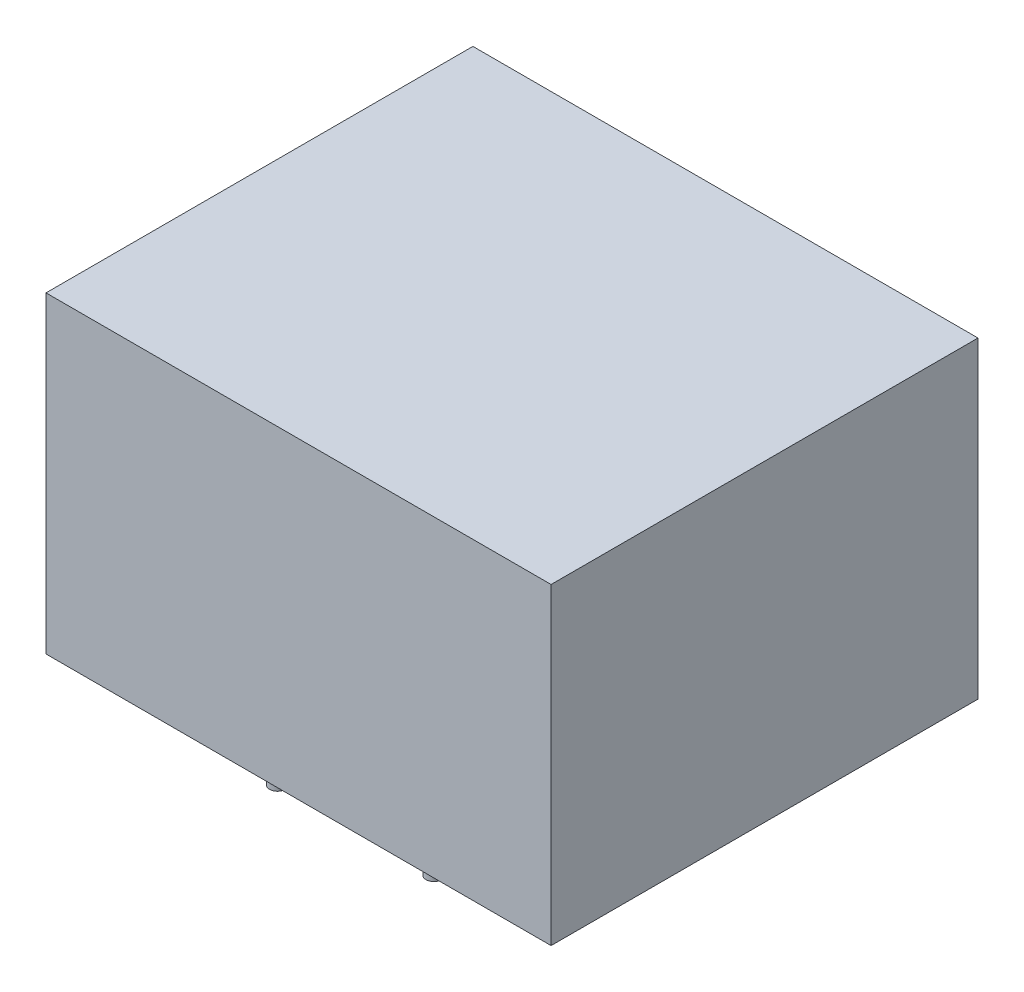
SolidWorks part; units mm, degrees
material "Hexcel AS4C (3000 Filaments)"
ref_plane "Front Plane" through (0, 0, 0) normal (0, 0, 1) x (1, 0, 0)
ref_plane "Top Plane" through (0, 0, 0) normal (0, 1, 0) x (1, 0, 0)
ref_plane "Right Plane" through (0, 0, 0) normal (1, 0, 0) x (0, 0, -1)
sketch "Sketch1" plane through (0, 0, 0) normal (0, 1, 0) x (1, 0, 0)
  line L1 (16.15, -13.65) -> (-16.15, -13.65)
  line L2 (16.15, -13.65) -> (16.15, 13.65)
  line L3 (16.15, 13.65) -> (-16.15, 13.65)
  line L4 (-16.15, -13.65) -> (-16.15, 13.65)
  line L5 (16.15, -13.65) -> (-16.15, 13.65) construction
  line L6 (16.15, 13.65) -> (-16.15, -13.65) construction
  point P0 (0, 0)
  dimension "D1" = 32.3
  dimension "D2" = 27.3
extrude "Base Extrusion" add sketch "Sketch1" along normal blind 20
sketch "Sketch2" plane through (0, 0, 0) normal (0, -1, 0) x (1, 0, 0)
  line L0 (-5, 10) -> (5, 10) construction
  line L1 (10, -10) -> (-10, -10) construction
  line L2 (0, -11) -> (0, 11) construction
  line L3 (0, 10) -> (0, -10) construction
  line L4 (11, 0) -> (-11, 0) construction
  circle A0 centre (-5, 10) radius 0.5
  circle A1 centre (5, 10) radius 0.5
  circle A2 centre (-10, -10) radius 0.5
  circle A3 centre (10, -10) radius 0.5
  point P8 (0, -10)
  point P11 (0, 10)
  point P14 (0, 0)
  dimension "D1" = 1
  dimension "D2" = 10
  dimension "D3" = 20
  dimension "D4" = 20
extrude "Pins" add sketch "Sketch2" along normal blind 3.5
